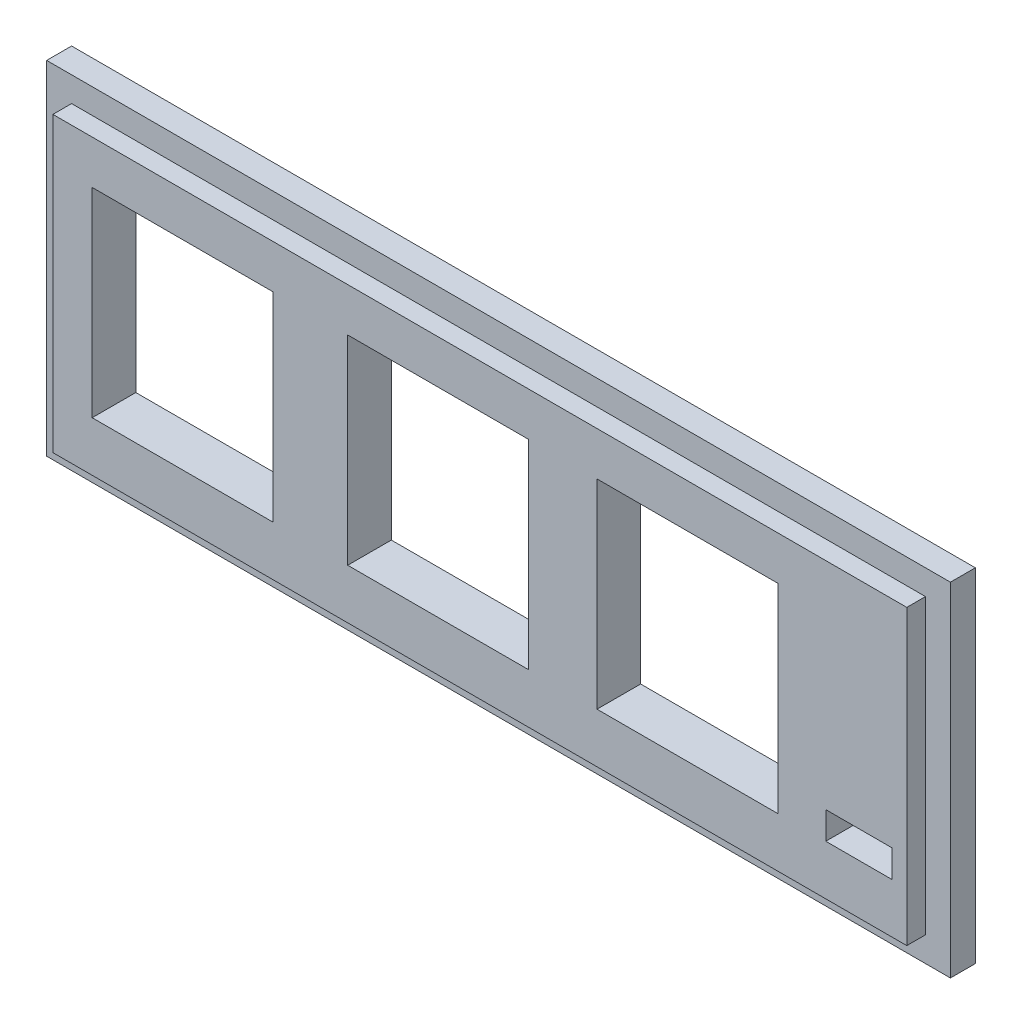
SolidWorks part; units mm, degrees
ref_plane "Přední rovina" through (0, 0, 0) normal (0, 0, 1) x (1, 0, 0)
ref_plane "Horní rovina" through (0, 0, 0) normal (0, 1, 0) x (1, 0, 0)
ref_plane "Pravá rovina" through (0, 0, 0) normal (1, 0, 0) x (0, 0, -1)
sketch "Skica1" plane through (0, 0, 0) normal (0, 0, 1) x (1, 0, 0)
  line L1 (-36.25, 13.75) -> (36.25, 13.75)
  line L2 (-36.25, 13.75) -> (-36.25, -13.75)
  line L3 (-36.25, -13.75) -> (36.25, -13.75)
  line L4 (36.25, 13.75) -> (36.25, -13.75)
  line L5 (-36.25, 13.75) -> (36.25, -13.75) construction
  line L6 (-36.25, -13.75) -> (36.25, 13.75) construction
  point P0 (0, 0)
  dimension "D1" = 72.5
  dimension "D2" = 27.5
extrude "Přidat vysunutím1" add sketch "Skica1" along normal blind 2
sketch "Skica2" plane through (0, 0, 2) normal (0, 0, 1) x (1, 0, 0)
  line L0 (-34.25, 11.75) -> (-34.25, -11.75)
  line L1 (-36.25, 13.75) -> (36.25, 13.75)
  line L2 (-36.25, 13.75) -> (-36.25, -13.75)
  line L3 (-36.25, -13.75) -> (36.25, -13.75)
  line L4 (36.25, 13.75) -> (36.25, -13.75)
  line L5 (-36.25, 13.75) -> (36.25, -13.75) construction
  line L6 (-36.25, -13.75) -> (36.25, 13.75) construction
  line L7 (-34.25, -11.75) -> (34.25, -11.75)
  line L8 (34.25, 11.75) -> (34.25, -11.75)
  line L9 (-34.25, 11.75) -> (34.25, 11.75)
  point P0 (0, 0)
  dimension "D1" = 2
extrude "Přidat vysunutím2" add sketch "Skica2" along normal blind 1.5 contours L9 L0 L7 L8
sketch "Skica3" plane through (0, 0, 3.5) normal (0, 0, 1) x (1, 0, 0)
  line L0 (-34.25, -7.75) -> (34.25, -7.75)
  line L1 (-34.25, 11.75) -> (-34.25, -11.75) construction
  line L2 (34.25, 11.75) -> (34.25, -11.75) construction
  line L3 (0, 0) -> (0, -7.75)
  line L4 (9.4, -7.75) -> (23.9, -7.75)
  line L5 (9.4, -7.75) -> (9.4, 8.25)
  line L6 (9.4, 8.25) -> (23.9, 8.25)
  line L7 (23.9, -7.75) -> (23.9, 8.25)
  line L8 (30.4, -7.75) -> (30.4, -6.65)
  line L9 (3.9, -7.75) -> (-10.6, -7.75)
  line L10 (3.9, -7.75) -> (3.9, 8.25)
  line L11 (3.9, 8.25) -> (-10.6, 8.25)
  line L12 (-10.6, -7.75) -> (-10.6, 8.25)
  line L13 (-16.6, -7.75) -> (-31.1, -7.75)
  line L14 (-16.6, -7.75) -> (-16.6, 8.25)
  line L15 (-16.6, 8.25) -> (-31.1, 8.25)
  line L16 (-31.1, -7.75) -> (-31.1, 8.25)
  line L18 (33.05, -5.55) -> (27.75, -5.55)
  line L19 (33.05, -5.55) -> (33.05, -7.75)
  line L20 (33.05, -7.75) -> (27.75, -7.75)
  line L21 (27.75, -5.55) -> (27.75, -7.75)
  line L22 (33.05, -5.55) -> (27.75, -7.75) construction
  line L23 (33.05, -7.75) -> (27.75, -5.55) construction
  dimension "D1" = 4
  dimension "D2" = 14.5
  dimension "D3" = 16
  dimension "D4" = 9.4
  dimension "D5" = 10.6
  dimension "D6" = 16.6
  dimension "D7" = 1.1
  dimension "D8" = 30.4
  dimension "D9" = 5.3
extrude "Odebrat vysunutím1" cut sketch "Skica3" against normal through all
